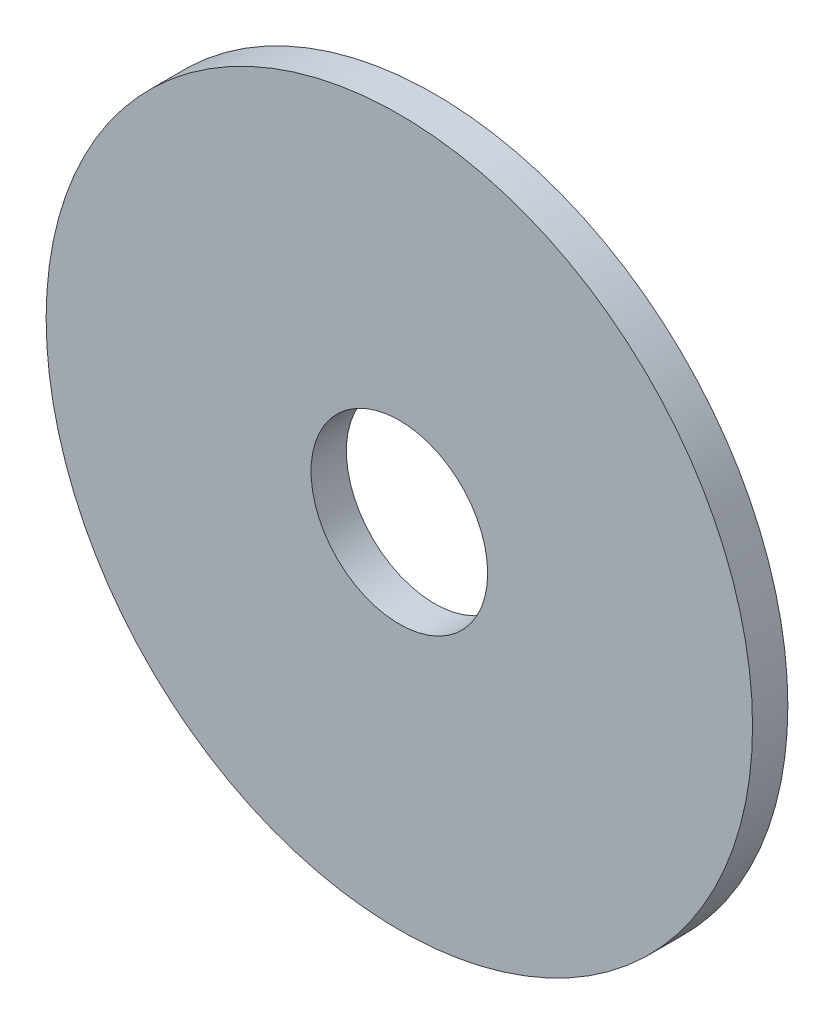
SolidWorks part; units mm, degrees
ref_plane "前视基准面" through (0, 0, 0) normal (0, 0, 1) x (1, 0, 0)
ref_plane "上视基准面" through (0, 0, 0) normal (0, 1, 0) x (1, 0, 0)
ref_plane "右视基准面" through (0, 0, 0) normal (1, 0, 0) x (0, 0, -1)
other "Configuration Table"
sketch "草图1" plane through (0, 0, 0) normal (0, 0, 1) x (1, 0, 0)
  circle A0 centre (0, 0) radius 10
  circle A1 centre (0, 0) radius 2.5
  dimension "D1" = 5
  dimension "D2" = 20
extrude "凸台-拉伸1" add sketch "草图1" along normal blind 1
